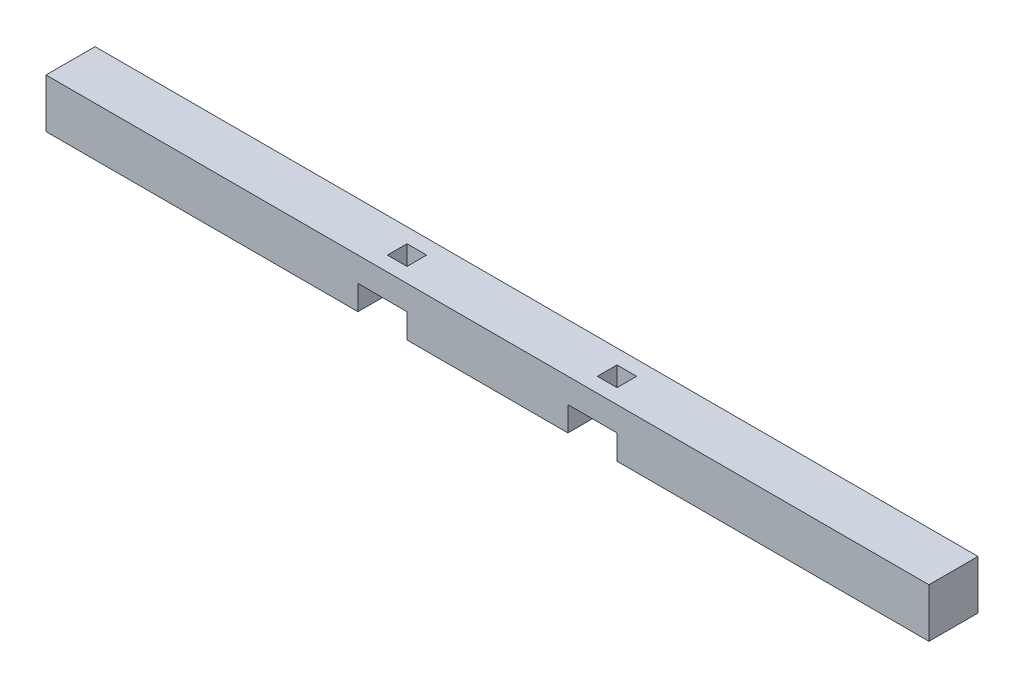
SolidWorks part; units mm, degrees
material "Balsa"
ref_plane "Plan de face" through (0, 0, 0) normal (0, 0, 1) x (1, 0, 0)
ref_plane "Plan de dessus" through (0, 0, 0) normal (0, 1, 0) x (1, 0, 0)
ref_plane "Plan de droite" through (0, 0, 0) normal (1, 0, 0) x (0, 0, -1)
sketch "Sketch1" plane through (0, 0, 0) normal (1, 0, 0) x (0, 0, -1)
  line L1 (0, 0) -> (25, 0)
  line L2 (0, 0) -> (0, 25)
  line L3 (0, 25) -> (25, 25)
  line L4 (25, 0) -> (25, 25)
  dimension "D1" = 25
  dimension "D2" = 25
extrude "Boss-Extrude1" add sketch "Sketch1" along normal blind 450
sketch "Sketch2" plane through (0, 25, 0) normal (0, 1, 0) x (1, 0, 0)
  line L0 (0, 12.5) -> (450, 12.5) construction
  line L1 (0, 25) -> (0, 0) construction
  line L2 (450, 25) -> (450, 0) construction
  line L3 (225, 25) -> (225, 0) construction
  line L4 (450, 25) -> (0, 25) construction
  line L5 (450, 0) -> (0, 0) construction
  line L6 (283.5, 17.5) -> (273.5, 17.5)
  line L7 (166.5, 7.5) -> (176.5, 7.5)
  line L8 (166.5, 7.5) -> (166.5, 17.5)
  line L9 (166.5, 17.5) -> (176.5, 17.5)
  line L10 (176.5, 7.5) -> (176.5, 17.5)
  line L11 (166.5, 7.5) -> (176.5, 17.5) construction
  line L12 (166.5, 17.5) -> (176.5, 7.5) construction
  line L13 (273.5, 7.5) -> (273.5, 17.5)
  line L14 (283.5, 7.5) -> (273.5, 7.5)
  line L15 (283.5, 7.5) -> (283.5, 17.5)
  point P12 (171.5, 12.5)
  dimension "D1" = 10
  dimension "D2" = 10
  dimension "D3" = 53.5
extrude "Cut-Extrude1" cut sketch "Sketch2" against normal through all
sketch "Sketch3" plane through (0, 0, 0) normal (0, -1, 0) x (1, 0, 0)
  line L0 (0, -12.5) -> (450, -12.5) construction
  line L1 (0, 0) -> (0, -25) construction
  line L2 (450, 0) -> (450, -25) construction
  line L3 (225, 0) -> (225, -25) construction
  line L4 (450, 0) -> (0, 0) construction
  line L5 (450, -25) -> (0, -25) construction
  line L6 (166.5, -17.5) -> (176.5, -7.5) construction
  line L7 (291, -25) -> (266, -25)
  line L8 (159, 0) -> (184, 0)
  line L9 (159, 0) -> (159, -25)
  line L10 (159, -25) -> (184, -25)
  line L11 (184, 0) -> (184, -25)
  line L12 (159, 0) -> (184, -25) construction
  line L13 (159, -25) -> (184, 0) construction
  line L14 (266, 0) -> (266, -25)
  line L15 (291, 0) -> (266, 0)
  line L16 (291, 0) -> (291, -25)
  point P16 (171.5, -12.5)
  dimension "D1" = 25
extrude "Cut-Extrude2" cut sketch "Sketch3" against normal blind 12.5
